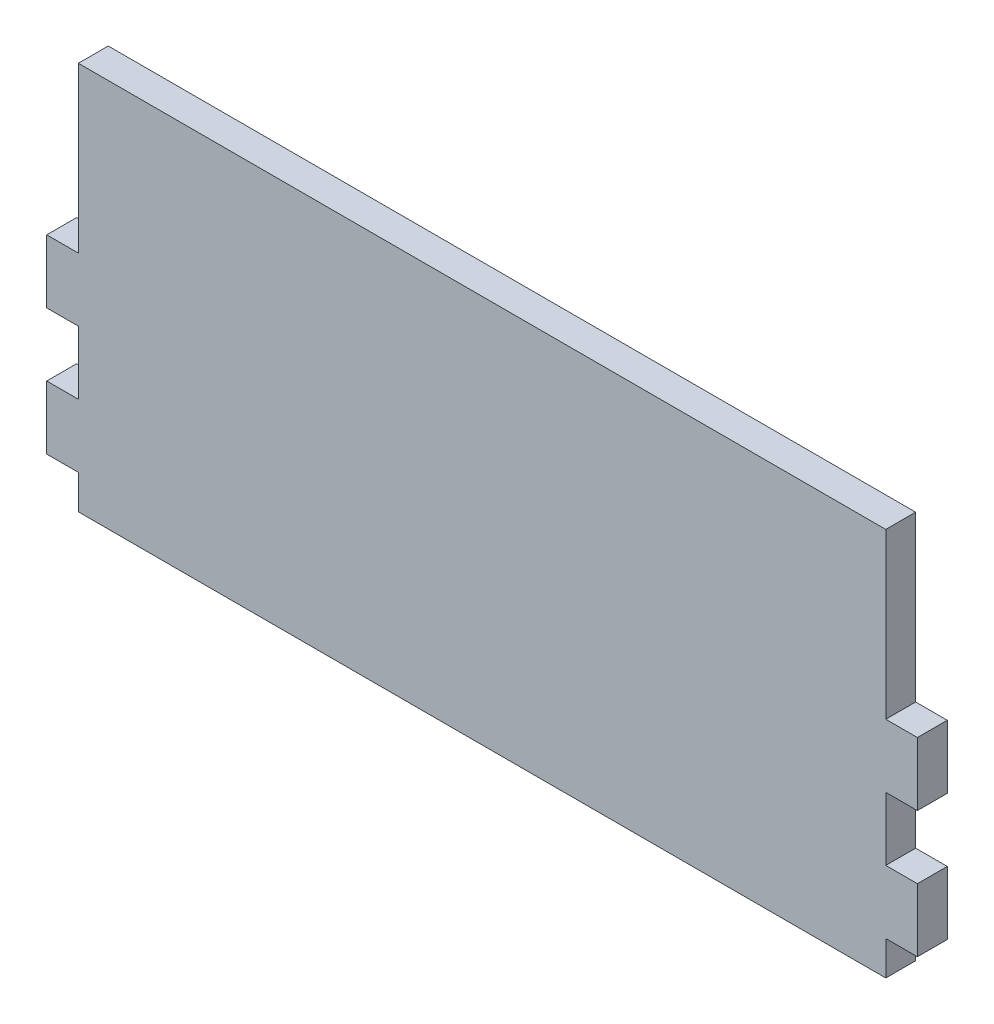
SolidWorks part; units mm, degrees
material "Acrylic (Medium-high impact)"
ref_plane "Front Plane" through (0, 0, 0) normal (0, 0, 1) x (1, 0, 0)
ref_plane "Top Plane" through (0, 0, 0) normal (0, 1, 0) x (1, 0, 0)
ref_plane "Right Plane" through (0, 0, 0) normal (1, 0, 0) x (0, 0, -1)
sketch "Sketch1" plane through (0, 0, 0) normal (0, 0, 1) x (1, 0, 0)
  line L0 (0, 0) -> (0, 3.4319)
  line L1 (0, 3.4319) -> (-3.175, 3.4319)
  line L2 (-3.175, 3.4319) -> (-3.175, 9.7819)
  line L3 (-3.175, 9.7819) -> (0, 9.7819)
  line L4 (0, 9.7819) -> (0, 16.1319)
  line L5 (0, 16.1319) -> (-3.175, 16.1319)
  line L6 (-3.175, 16.1319) -> (-3.175, 22.4819)
  line L7 (-3.175, 22.4819) -> (0, 22.4819)
  line L8 (40.5, 38.9752) -> (40.5, 0) construction
  line L9 (81, 0) -> (0, 0)
  line L10 (0, 22.4819) -> (0, 38.9752)
  line L11 (0, 38.9752) -> (81, 38.9752)
  line L12 (81, 22.4819) -> (81, 38.9752)
  line L13 (84.175, 22.4819) -> (81, 22.4819)
  line L14 (84.175, 16.1319) -> (84.175, 22.4819)
  line L15 (81, 16.1319) -> (84.175, 16.1319)
  line L16 (81, 9.7819) -> (81, 16.1319)
  line L17 (84.175, 9.7819) -> (81, 9.7819)
  line L18 (84.175, 3.4319) -> (84.175, 9.7819)
  line L19 (81, 3.4319) -> (84.175, 3.4319)
  line L20 (81, 0) -> (81, 3.4319)
  dimension "D1" = 40.5
  dimension "D2" = 3.175
  dimension "D3" = 6.35
  dimension "D4" = 3.4319
  dimension "D5" = 16.4933
extrude "Boss-Extrude1" add sketch "Sketch1" along normal blind 2.9972
